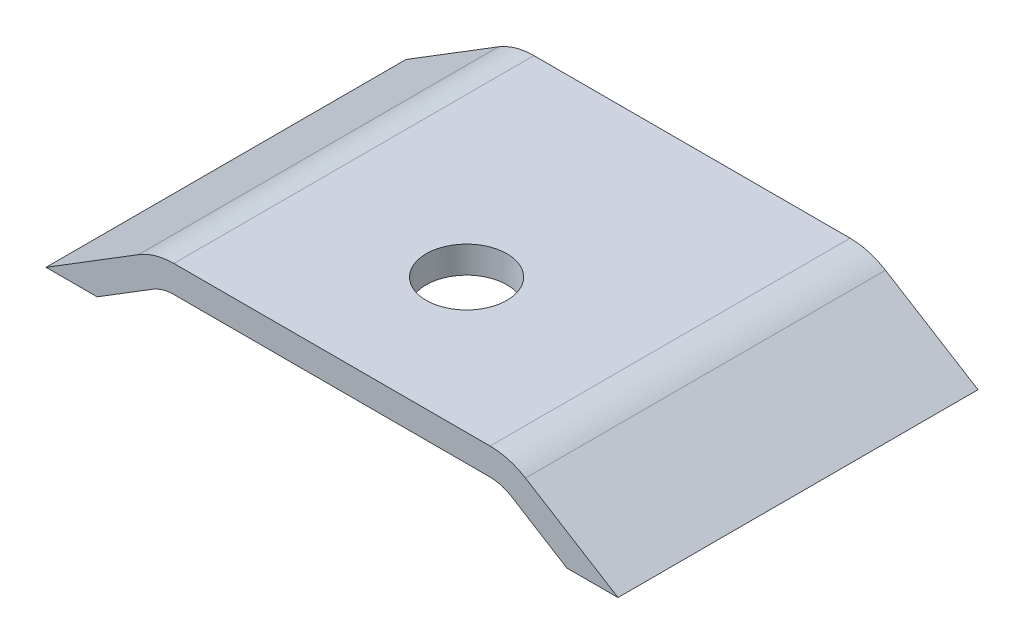
SolidWorks part; units mm, degrees
ref_plane "Front Plane" through (0, 0, 0) normal (0, 0, 1) x (1, 0, 0)
ref_plane "Top Plane" through (0, 0, 0) normal (0, 1, 0) x (1, 0, 0)
ref_plane "Right Plane" through (0, 0, 0) normal (1, 0, 0) x (0, 0, -1)
sketch "Sketch1" plane through (0, 0, 0) normal (0, 0, 1) x (1, 0, 0)
  line L0 (-53.975, -6.35) -> (-33.4494, 6.35)
  line L1 (53.975, -6.35) -> (-53.975, -6.35) construction
  line L2 (53.975, -6.35) -> (53.975, 6.35) construction
  line L3 (53.975, 6.35) -> (-53.975, 6.35) construction
  line L4 (-53.975, -6.35) -> (-53.975, 6.35) construction
  line L5 (53.975, -6.35) -> (-53.975, 6.35) construction
  line L6 (53.975, 6.35) -> (-53.975, -6.35) construction
  line L7 (-33.4494, 6.35) -> (33.4494, 6.35)
  line L8 (33.4494, 6.35) -> (53.975, -6.35)
  line L9 (53.975, -6.35) -> (-53.975, -6.35)
  point P0 (0, 0)
  dimension "D1" = 107.95
  dimension "D2" = 12.7
  dimension "D3" = 148.253
extrude "Boss-Extrude1" add sketch "Sketch1" along normal blind 67.945
fillet "Fillet1" radius 12.7 2 edges at (-33.4494, 6.35, 33.9725) (33.4494, 6.35, 33.9725)
sketch "Sketch3" plane through (0, 0, 67.945) normal (0, 0, 1) x (1, 0, 0)
  line L27 (-51.3021, -10.6699) -> (51.3021, -10.6699)
  line L30 (51.3021, -10.6699) -> (33.8475, 0.1299)
  line L31 (29.8381, 1.27) -> (-29.8381, 1.27)
  line L32 (-33.8475, 0.1299) -> (-51.3021, -10.6699)
  line L33 (51.3021, -10.6699) -> (33.8475, 0.1299)
  line L34 (29.8381, 1.27) -> (-29.8381, 1.27)
  line L35 (-33.8475, 0.1299) -> (-51.3021, -10.6699)
  arc A17 (33.8475, 0.1299) -> (29.8381, 1.27) centre (29.8381, -6.35) ccw
  arc A18 (-29.8381, 1.27) -> (-33.8475, 0.1299) centre (-29.8381, -6.35) ccw
  arc A19 (33.8475, 0.1299) -> (29.8381, 1.27) centre (29.8381, -6.35) ccw
  arc A20 (-29.8381, 1.27) -> (-33.8475, 0.1299) centre (-29.8381, -6.35) ccw
  dimension "D1" = 5.08
extrude "Cut-Extrude1" cut sketch "Sketch3" against normal up to next
ref_plane "Plane1" through (0, 0, 33.9725) normal (0, 0, -1) x (-1, 0, 0)
sketch "Sketch5" plane through (0, 6.35, 0) normal (0, 1, 0) x (1, 0, 0)
  line L0 (29.8381, -67.945) -> (-29.8381, -67.945) construction
  circle A0 centre (0, -42.545) radius 7.62
  dimension "D1" = 15.24
  dimension "D2" = 25.4
extrude "Cut-Extrude2" cut sketch "Sketch5" against normal up to next
